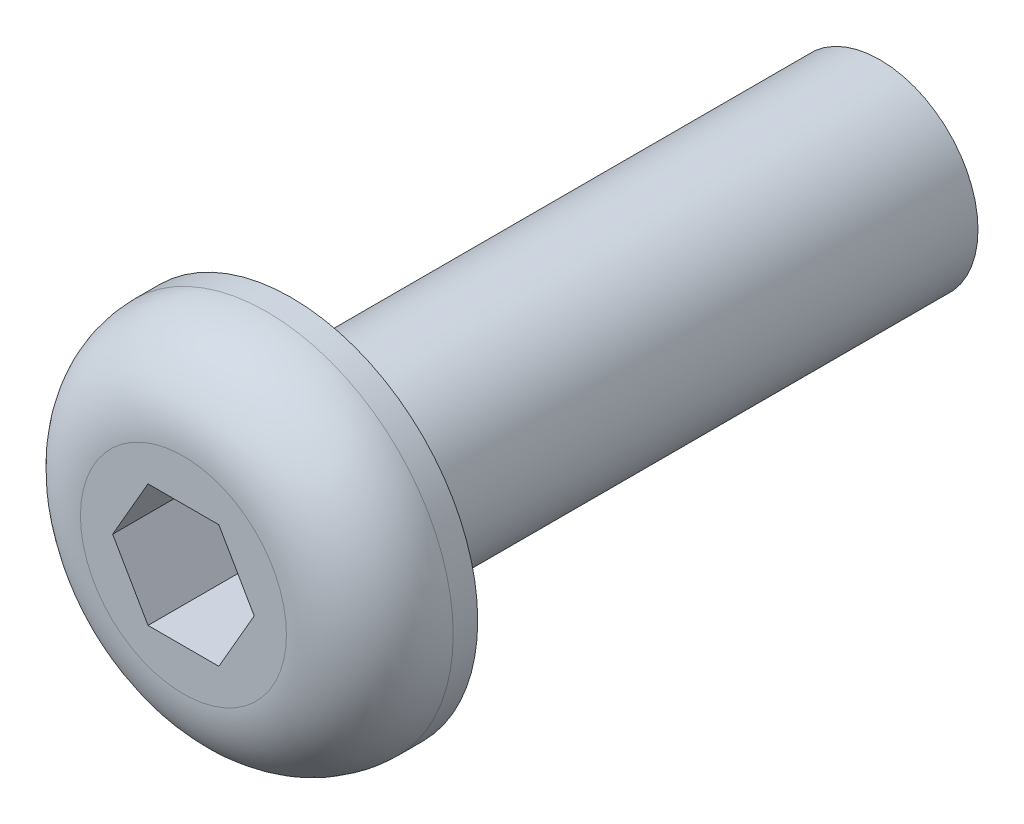
SolidWorks part; units mm, degrees
material "AISI 304"
ref_plane "Front Plane" through (0, 0, 0) normal (0, 0, 1) x (1, 0, 0)
ref_plane "Top Plane" through (0, 0, 0) normal (0, 1, 0) x (1, 0, 0)
ref_plane "Right Plane" through (0, 0, 0) normal (1, 0, 0) x (0, 0, -1)
sketch "Sketch1" plane through (0, 0, 0) normal (0, 0, 1) x (1, 0, 0)
  circle A0 centre (0, 0) radius 2
  dimension "D1" = 4
extrude "Extrude1" add sketch "Sketch1" against normal blind 12
sketch "Sketch2" plane through (0, 0, 0) normal (1, 0, 0) x (0, 0, -1)
  line L0 (0, 0) -> (-10.9859, 0) construction
  line L1 (0, 0) -> (0, 3.8)
  line L2 (0, 3.8) -> (-0.5, 3.8)
  line L3 (-2.2, 0) -> (-2.2, 2.1)
  line L4 (0, 0) -> (-2.2, 0)
  arc A0 (-2.2, 2.1) -> (-0.5, 3.8) centre (-0.5, 2.1) cw
  dimension "D1" = 2.2
  dimension "D2" = 7.6
  dimension "D3" = 0.5
revolve "Revolve1" add sketch "Sketch2" angle 360 about L0
sketch "Sketch3" plane through (0, 0, 2.2) normal (0, 0, 1) x (1, 0, 0)
  line L1 (-0.7217, 1.25) -> (-1.4434, 0)
  line L2 (-1.4434, 0) -> (-0.7217, -1.25)
  line L3 (-0.7217, -1.25) -> (0.7217, -1.25)
  line L4 (0.7217, -1.25) -> (1.4434, 0)
  line L5 (1.4434, 0) -> (0.7217, 1.25)
  line L6 (0.7217, 1.25) -> (-0.7217, 1.25)
  circle A0 centre (0, 0) radius 1.25 construction
  dimension "D1" = 2.5
extrude "Cut-Extrude1" cut sketch "Sketch3" against normal blind 2
